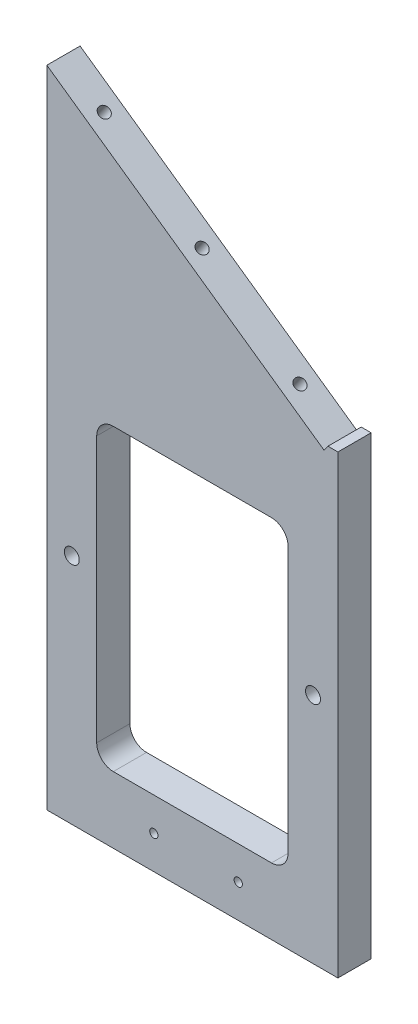
SolidWorks part; units mm, degrees
ref_plane "前视基准面" through (0, 0, 0) normal (0, 0, 1) x (1, 0, 0)
ref_plane "上视基准面" through (0, 0, 0) normal (0, 1, 0) x (1, 0, 0)
ref_plane "右视基准面" through (0, 0, 0) normal (1, 0, 0) x (0, 0, -1)
sketch "草图1" plane through (0, 0, 0) normal (0, 0, 1) x (1, 0, 0)
  line L0 (-1000, 0) -> (49000, 0) construction
  line L1 (0, 0) -> (-83.4513, 58.6505)
  line L2 (-83.4513, 58.6505) -> (-83.4513, -135.4795)
  line L3 (-83.4513, -135.4795) -> (4.15, -135.4795)
  line L4 (4.15, -135.4795) -> (4.15, 1.6363)
  line L5 (4.15, 1.6363) -> (1.15, 1.6363)
  line L6 (1.15, 1.6363) -> (0, 0)
  dimension "D1" = 35.1
  dimension "D2" = 102
  dimension "D3" = 2
  dimension "D4" = 3
  dimension "D5" = 194.13
extrude "凸台-拉伸1" add sketch "草图1" along normal blind 10
hole_wizard "M4 螺纹孔1" positions "草图3" profile "草图2" tap size "M4" standard "ISO"
sketch "草图3" plane through (0, 0, 0) normal (0.575, 0.8181, 0) x (-0.8181, 0.575, 0)
  line L0 (0, 0) -> (102, 0) construction
  line L1 (0, 10) -> (0, 0) construction
  point P0 (15, 5)
  dimension "D1" = 5
  dimension "D2" = 15
sketch "草图2" plane through (-12.2722, 8.6251, 5) normal (0, 0, 1) x (-0.8181, 0.575, 0)
  line L0 (0, 0) -> (0, 11.0914)
  line L1 (0, 11.0914) -> (1.65, 10.1)
  line L2 (1.65, 10.1) -> (1.65, 0)
  line L5 (1.65, 0) -> (0, 0)
  line L10 (0, 11.0914) -> (-1.65, 10.1) construction
  line L11 (0, -6.35) -> (0, 107.95) construction
  dimension "螺纹孔钻头直径" = 3.3
  dimension "螺纹孔钻头深度" = 10.1
  dimension "导头角度" = 118
cosmetic thread "孔螺蚊线1" parameters "D1"=8, "D2"=4
pattern_linear "阵列(线性)1" count 3 spacing 36 along (-0.8181, 0.575, 0) of "M4 螺纹孔1"
sketch "草图4" plane through (0, 0, 10) normal (0, 0, 1) x (1, 0, 0)
  line L0 (-83.4513, 58.6505) -> (-83.4513, -135.4795) construction
  line L1 (-63.4513, -115.4795) -> (-15.85, -115.4795)
  line L2 (-68.4513, -110.4795) -> (-68.4513, -30.4795)
  line L3 (-63.4513, -25.4795) -> (-15.85, -25.4795)
  line L4 (-10.85, -110.4795) -> (-10.85, -30.4795)
  line L5 (4.15, -135.4795) -> (4.15, 1.6363) construction
  line L6 (-83.4513, -135.4795) -> (4.15, -135.4795) construction
  arc A0 (-68.4513, -110.4795) -> (-63.4513, -115.4795) centre (-63.4513, -110.4795) ccw
  arc A1 (-15.85, -115.4795) -> (-10.85, -110.4795) centre (-15.85, -110.4795) ccw
  arc A2 (-10.85, -30.4795) -> (-15.85, -25.4795) centre (-15.85, -30.4795) ccw
  arc A3 (-68.4513, -30.4795) -> (-63.4513, -25.4795) centre (-63.4513, -30.4795) cw
  dimension "D4" = 5
  dimension "D1" = 15
  dimension "D2" = 15
  dimension "D3" = 20
  dimension "D5" = 90
extrude "切除-拉伸1" cut sketch "草图4" against normal through all
hole_wizard "M6 螺纹孔1" positions "草图6" profile "草图5" tap size "M6" standard "ISO"
sketch "草图6" plane through (0, -135.4795, 0) normal (0, -1, 0) x (1, 0, 0)
  line L0 (4.15, 10) -> (4.15, 0) construction
  line L1 (-83.4513, 10) -> (4.15, 10) construction
  point P0 (-5.85, 5)
  dimension "D1" = 10
  dimension "D2" = 5
sketch "草图5" plane through (-5.85, -135.4795, 5) normal (1, 0, 0) x (0, 0, -1)
  line L0 (0, 0) -> (0, 16.5022)
  line L1 (0, 16.5022) -> (2.5, 15)
  line L2 (2.5, 15) -> (2.5, 0)
  line L5 (2.5, 0) -> (0, 0)
  line L10 (0, 16.5022) -> (-2.5, 15) construction
  line L11 (0, -6.35) -> (0, 107.95) construction
  dimension "螺纹孔钻头直径" = 5
  dimension "螺纹孔钻头深度" = 15
  dimension "导头角度" = 118
cosmetic thread "孔螺蚊线2" parameters "D1"=12, "D2"=6
pattern_linear "阵列(线性)2" count 3 spacing 33.8 along (-1, 0, 0) of "M6 螺纹孔1"
sketch "草图7" plane through (0, 0, 10) normal (0, 0, 1) x (1, 0, 0)
  line L0 (-1068.4513, -65.4795) -> (48931.5487, -65.4795) construction
  line L2 (-83.4513, -135.4795) -> (4.15, -135.4795) construction
  line L3 (-83.4513, 58.6505) -> (-83.4513, -135.4795) construction
  line L4 (4.15, -135.4795) -> (4.15, 1.6363) construction
  circle A0 centre (-75.9513, -65.4795) radius 2.25
  circle A1 centre (-3.35, -65.4795) radius 2.25
  dimension "D2" = 4.5
  dimension "D1" = 70
  dimension "D3" = 7.5
  dimension "D4" = 7.5
extrude "切除-拉伸2" cut sketch "草图7" against normal through all
hole_wizard "M3 螺纹孔1" positions "草图9" profile "草图8" tap size "M3" standard "ISO" end condition through all
sketch "草图9" plane through (0, 0, 0) normal (0, 0, -1) x (-1, 0, 0)
  line L0 (63.4513, -115.4795) -> (15.85, -115.4795) construction
  line L1 (-4.15, -135.4795) -> (-4.15, 1.6363) construction
  point P0 (25.85, -125.4795)
  dimension "D1" = 10
  dimension "D2" = 30
sketch "草图8" plane through (-25.85, -125.4795, 0) normal (1, 0, 0) x (0, 1, 0)
  line L0 (0, 0) -> (0, 10)
  line L1 (0, 10) -> (1.25, 10)
  line L2 (1.25, 10) -> (1.25, 0)
  line L5 (1.25, 0) -> (0, 0)
  line L11 (0, -6.35) -> (0, 107.95) construction
  dimension "通孔螺纹孔钻头直径" = 2.5
  dimension "通孔螺纹孔钻头深度" = 10
cosmetic thread "孔螺蚊线3" parameters "D2"=3
pattern_linear "阵列(线性)3" count 2 spacing 25.4 along (-1, 0, 0) of "M3 螺纹孔1"
